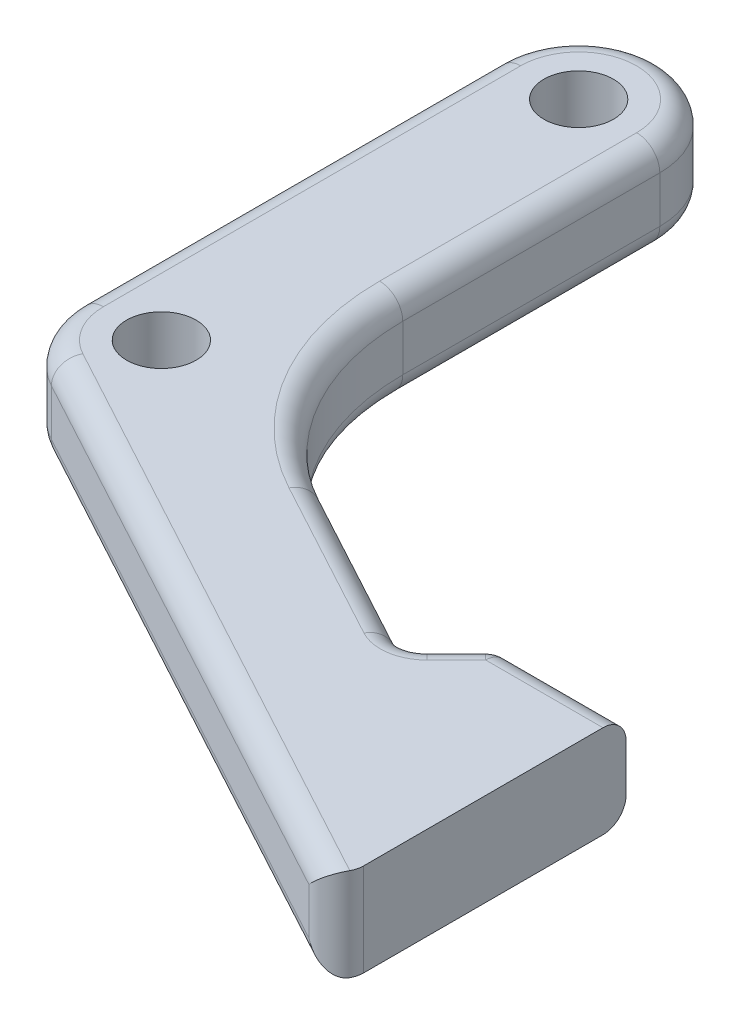
SolidWorks part; units mm, degrees
ref_plane "Front Plane" through (0, 0, 0) normal (0, 0, 1) x (1, 0, 0)
ref_plane "Top Plane" through (0, 0, 0) normal (0, 1, 0) x (1, 0, 0)
ref_plane "Right Plane" through (0, 0, 0) normal (1, 0, 0) x (0, 0, -1)
sketch "Sketch1" plane through (0, 0, 0) normal (0, 1, 0) x (1, 0, 0)
  line L0 (0, 18) -> (0, 0) construction
  line L1 (3.5, 18.0002) -> (3.5007, 6.9116)
  line L2 (-3.5, 17.9998) -> (-3.4989, 0)
  line L3 (-1.664, -3.0779) -> (24, -16.9527)
  line L5 (24, -3.9527) -> (18.9431, -3.9527)
  line L6 (18.236, -4.2456) -> (16.9649, -5.5166)
  line L7 (15.7822, -5.6892) -> (8.7449, -1.8846)
  line L8 (24, -3.9527) -> (24, -16.9527)
  circle A0 centre (0, 0) radius 1.5
  circle A1 centre (0, 18) radius 1.5
  arc A2 (3.5, 18.0002) -> (-3.5, 17.9998) centre (0, 18) ccw
  arc A3 (-3.4989, 0) -> (-1.664, -3.0779) centre (0, 0) ccw
  arc A4 (3.5007, 6.9116) -> (8.7449, -1.8846) centre (13.5007, 6.9122) ccw
  arc A5 (18.9431, -3.9527) -> (18.236, -4.2456) centre (18.9431, -4.9527) ccw
  arc A6 (16.9649, -5.5166) -> (15.7822, -5.6892) centre (16.2578, -4.8095) cw
  point P5 (0, 9)
  dimension "D1" = 3
  dimension "D2" = 3
  dimension "D7" = 10
  dimension "D8" = 1
  dimension "D3" = 18
  dimension "D4" = 7
  dimension "D5" = 135
  dimension "D6" = 13
  dimension "D9" = 24
  dimension "D10" = 6
  dimension "D11" = 8
extrude "Boss-Extrude1" add sketch "Sketch1" along normal blind 4
fillet "Fillet1" radius 1 23 edges at (21.4715, 4, 3.9527) (18.5604, 4, 4.0288) (17.6004, 4, 4.8811) (16.4022, 4, 5.7991) (12.2636, 4, 3.7869) (4.9113, 4, -1.7913) (3.5003, 4, -12.4559) (-0.0002, 4, -21.5) (-3.0054, 4, 1.7917) (21.4715, 0, 3.9527) (18.5604, 0, 4.0288) (17.6004, 0, 4.8811) (16.4022, 0, 5.7991) (12.2636, 0, 3.7869) (4.9113, 0, -1.7913) (3.5003, 0, -12.4559) (-0.0002, 0, -21.5) (-3.0054, 0, 1.7917) (-3.4995, 4, -8.9999) (-3.4995, 0, -8.9999) (11.168, 4, 10.0153) (24, 2, 16.9527) (11.168, 0, 10.0153)
